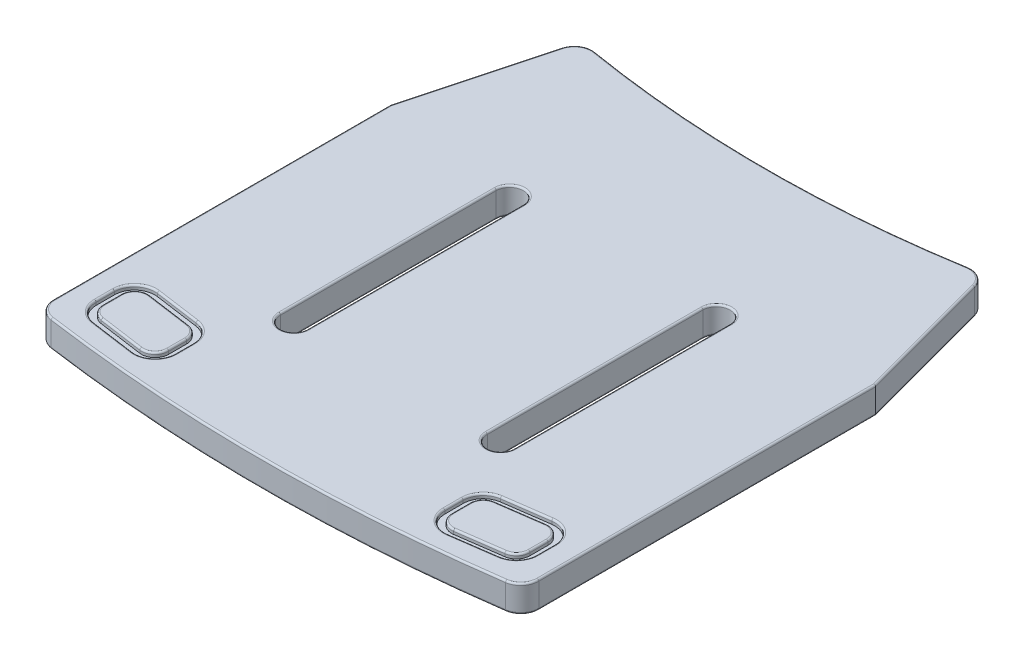
SolidWorks part; units mm, degrees
ref_plane "Front Plane" through (0, 0, 0) normal (0, 0, 1) x (1, 0, 0)
ref_plane "Top Plane" through (0, 0, 0) normal (0, 1, 0) x (1, 0, 0)
ref_plane "Right Plane" through (0, 0, 0) normal (1, 0, 0) x (0, 0, -1)
sketch "Sketch1" plane through (0, 0, 0) normal (0, 1, 0) x (1, 0, 0)
  line L0 (-11.5, 39) -> (-11.5, 15) construction
  line L1 (-10, 39) -> (-10, 15)
  line L2 (-13, 39) -> (-13, 15)
  line L3 (27, 0.004) -> (-27, 0.004) construction
  line L4 (-27, 3.7348) -> (-27, 41.2148)
  line L5 (0, 0) -> (0, 56) construction
  line L6 (22.9726, 56.2452) -> (27, 41.2148)
  line L7 (-22.9726, 56.2452) -> (-27, 41.2148)
  line L8 (27, 3.7348) -> (27, 41.2148)
  line L9 (11.5, 39) -> (11.5, 15) construction
  line L10 (10, 39) -> (10, 15)
  line L11 (13, 39) -> (13, 15)
  arc A0 (-10, 39) -> (-13, 39) centre (-11.5, 39) ccw
  arc A1 (-13, 15) -> (-10, 15) centre (-11.5, 15) ccw
  arc A2 (-25.2762, 1.754) -> (25.2762, 1.754) centre (0, 183) ccw
  arc A3 (-20.7146, 57.7007) -> (20.7146, 57.7007) centre (0, 183) ccw
  arc A4 (-27, 3.7348) -> (-25.2762, 1.754) centre (-25, 3.7348) ccw
  arc A5 (-22.9726, 56.2452) -> (-20.7146, 57.7007) centre (-21.0408, 55.7275) cw
  arc A6 (22.9726, 56.2452) -> (20.7146, 57.7007) centre (21.0408, 55.7275) ccw
  arc A7 (27, 3.7348) -> (25.2762, 1.754) centre (25, 3.7348) cw
  arc A8 (10, 39) -> (13, 39) centre (11.5, 39) cw
  arc A9 (13, 15) -> (10, 15) centre (11.5, 15) cw
  point P2 (-11.5, 27)
  point P16 (-27, 2.0028)
  point P20 (-22.5, 58.009)
  point P29 (22.5, 58.009)
  point P30 (27, 2.0028)
  point P33 (11.5, 27)
  dimension "D7" = 22.5
  dimension "D10" = 2
  dimension "D3" = 183
  dimension "D5" = 127
  dimension "D8" = 15
  dimension "D1" = 3
  dimension "D2" = 10
  dimension "D4" = 24
  dimension "D6" = 15
  dimension "D11" = 27
extrude "Boss-Extrude1" add sketch "Sketch1" along normal blind 3
fillet "Fillet1" radius 0.2 36 edges at (13, 0, -27) (11.5, 0, -13.5) (10, 0, -27) (11.5, 0, -40.5) (0, 0, 0) (26.5087, 0, -2.4219) (27, 0, -22.4748) (24.9863, 0, -48.73) (22.1244, 0, -57.4085) (0, 0, -56) (-22.1244, 0, -57.4085) (-24.9863, 0, -48.73) (-27, 0, -22.4748) (-26.5087, 0, -2.4219) (-10, 0, -27) (-11.5, 0, -13.5) (-13, 0, -27) (-11.5, 0, -40.5) (11.5, 3, -13.5) (13, 3, -27) (11.5, 3, -40.5) (10, 3, -27) (-11.5, 3, -13.5) (-10, 3, -27) (-11.5, 3, -40.5) (-13, 3, -27) (-27, 3, -22.4748) (-24.9863, 3, -48.73) (-22.1244, 3, -57.4085) (0, 3, -56) (22.1244, 3, -57.4085) (24.9863, 3, -48.73) (27, 3, -22.4748) (26.5087, 3, -2.4219) (0, 3, 0) (-26.5087, 3, -2.4219)
sketch "Sketch2" plane through (0, 3, 0) normal (0, 1, 0) x (1, 0, 0)
  line L0 (-23.75, 8.0159) -> (-23.75, 5.9962)
  line L1 (-22.4588, 4.5108) -> (-17.4588, 3.8081)
  line L2 (-15.75, 5.2935) -> (-15.75, 7.3132)
  line L3 (-17.0412, 8.7986) -> (-22.0412, 9.5013)
  line L4 (0, -55) -> (0, 55) construction
  line L5 (-16.9369, 9.5413) -> (-21.9369, 10.244)
  line L6 (-24.5, 8.0159) -> (-24.5, 5.9962)
  line L7 (-22.5631, 3.7681) -> (-17.5631, 3.0654)
  line L8 (-15, 5.2935) -> (-15, 7.3132)
  line L9 (0, 0) -> (0, 8.6073) construction
  line L10 (15, 5.2935) -> (15, 7.3132)
  line L11 (22.5631, 3.7681) -> (17.5631, 3.0654)
  line L12 (24.5, 8.0159) -> (24.5, 5.9962)
  line L13 (16.9369, 9.5413) -> (21.9369, 10.244)
  line L14 (17.0412, 8.7986) -> (22.0412, 9.5013)
  line L15 (15.75, 5.2935) -> (15.75, 7.3132)
  line L16 (22.4588, 4.5108) -> (17.4588, 3.8081)
  line L17 (23.75, 8.0159) -> (23.75, 5.9962)
  line L18 (0, 0) -> (-29.4556, 0) construction
  arc A0 (-15.75, 7.3132) -> (-17.0412, 8.7986) centre (-17.25, 7.3132) ccw
  arc A1 (-17.4588, 3.8081) -> (-15.75, 5.2935) centre (-17.25, 5.2935) ccw
  arc A2 (-23.75, 5.9962) -> (-22.4588, 4.5108) centre (-22.25, 5.9962) ccw
  arc A3 (-23.75, 8.0159) -> (-22.0412, 9.5013) centre (-22.25, 8.0159) cw
  arc A4 (-24.5, 8.0159) -> (-21.9369, 10.244) centre (-22.25, 8.0159) cw
  arc A5 (-24.5, 5.9962) -> (-22.5631, 3.7681) centre (-22.25, 5.9962) ccw
  arc A6 (-17.5631, 3.0654) -> (-15, 5.2935) centre (-17.25, 5.2935) ccw
  arc A7 (-15, 7.3132) -> (-16.9369, 9.5413) centre (-17.25, 7.3132) ccw
  arc A8 (15, 7.3132) -> (16.9369, 9.5413) centre (17.25, 7.3132) cw
  arc A9 (17.5631, 3.0654) -> (15, 5.2935) centre (17.25, 5.2935) cw
  arc A10 (24.5, 5.9962) -> (22.5631, 3.7681) centre (22.25, 5.9962) cw
  arc A11 (24.5, 8.0159) -> (21.9369, 10.244) centre (22.25, 8.0159) ccw
  arc A12 (23.75, 8.0159) -> (22.0412, 9.5013) centre (22.25, 8.0159) ccw
  arc A13 (23.75, 5.9962) -> (22.4588, 4.5108) centre (22.25, 5.9962) cw
  arc A14 (17.4588, 3.8081) -> (15.75, 5.2935) centre (17.25, 5.2935) cw
  arc A15 (15.75, 7.3132) -> (17.0412, 8.7986) centre (17.25, 7.3132) cw
  dimension "D3" = 1.5
  dimension "D1" = 8
  dimension "D2" = 5
  dimension "D4" = 8
  dimension "D6" = 15
  dimension "D5" = 0.75
extrude "Cut-Extrude1" cut sketch "Sketch2" against normal blind 0.5
fillet "Fillet2" radius 0.2 32 edges at (15.5519, 3, -8.7893) (19.4369, 3, -9.8927) (23.7261, 3, -9.714) (24.5, 3, -7.0061) (23.9481, 3, -4.5201) (20.0631, 3, -3.4168) (15.7739, 3, -3.5954) (16.1179, 3, -8.2973) (19.5412, 3, -9.1499) (23.2341, 3, -9.148) (23.75, 3, -7.0061) (23.3821, 3, -5.0122) (19.9588, 3, -4.1595) (16.2659, 3, -4.1615) (-23.7261, 3, -9.714) (-19.4369, 3, -9.8927) (-15.5519, 3, -8.7893) (-15, 3, -6.3034) (-15.7739, 3, -3.5954) (-20.0631, 3, -3.4168) (-23.9481, 3, -4.5201) (-23.2341, 3, -9.148) (-19.5412, 3, -9.1499) (-16.1179, 3, -8.2973) (-15.75, 3, -6.3034) (-16.2659, 3, -4.1615) (-19.9588, 3, -4.1595) (-23.3821, 3, -5.0122) (15, 3, -6.3034) (15.75, 3, -6.3034) (-24.5, 3, -7.0061) (-23.75, 3, -7.0061)
ref_plane "Plane1" through (0, 0, -39) normal (0, 0, 1) x (0, -1, 0)
